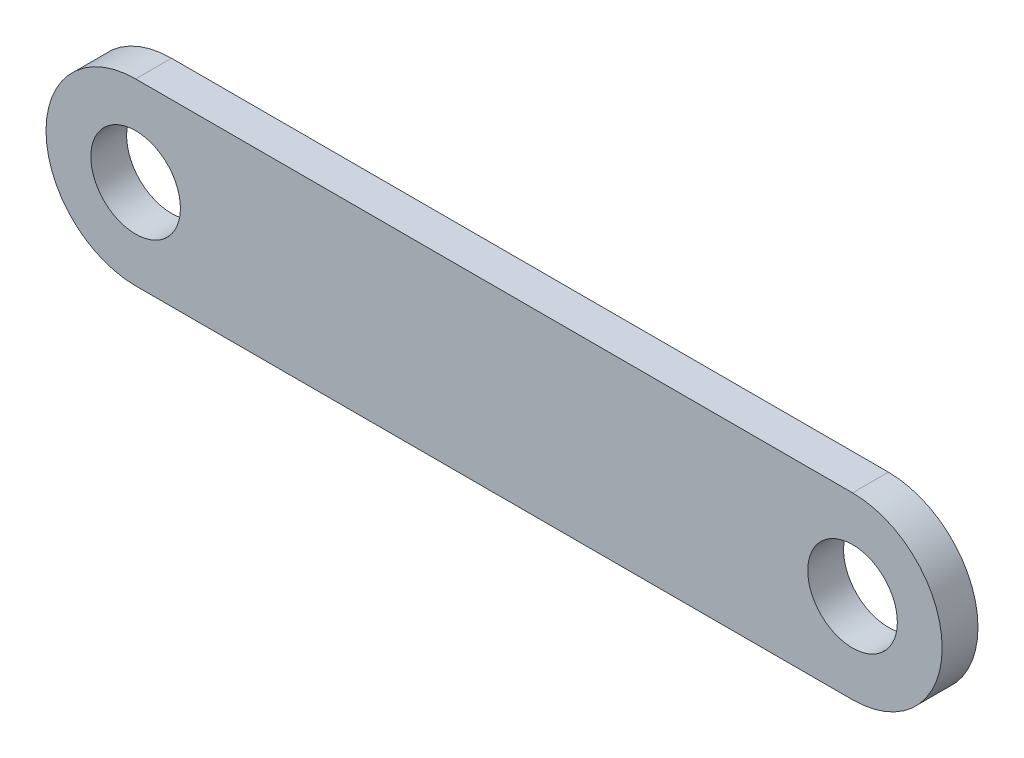
SolidWorks part; units mm, degrees
material "AISI 1020"
ref_plane "Face" through (0, 0, 0) normal (0, 0, 1) x (1, 0, 0)
ref_plane "Dessus" through (0, 0, 0) normal (0, 1, 0) x (1, 0, 0)
ref_plane "Droite" through (0, 0, 0) normal (1, 0, 0) x (0, 0, -1)
sketch "Esquisse1" plane through (0, 0, 0) normal (0, 0, 1) x (1, 0, 0)
  line L0 (-20, 5) -> (20, 5)
  line L1 (-20, -5) -> (20, -5)
  circle A0 centre (-20, 0) radius 2.5
  arc A1 (-20, 5) -> (-20, -5) centre (-20, 0) ccw
  circle A2 centre (20, 0) radius 2.5
  arc A3 (20, -5) -> (20, 5) centre (20, 0) ccw
  dimension "D1" = 5
  dimension "D2" = 20
  dimension "D3" = 20
extrude "Boss.-Extru.1" add sketch "Esquisse1" along normal blind 2
